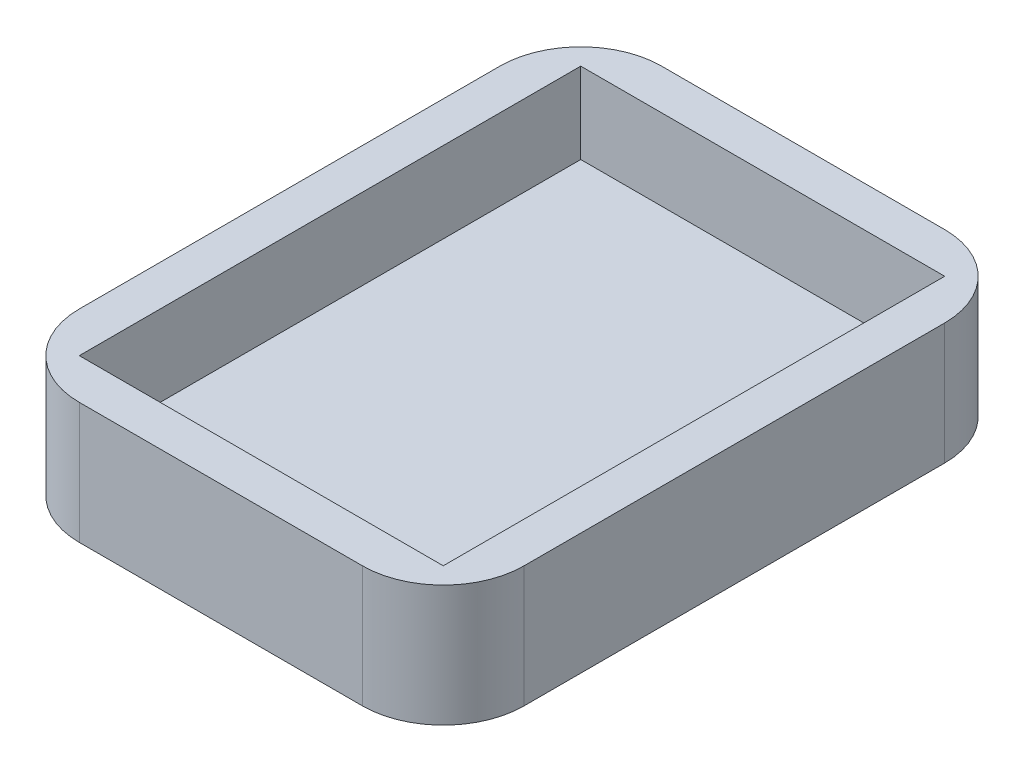
SolidWorks part; units mm, degrees
ref_plane "Front Plane" through (0, 0, 0) normal (0, 0, 1) x (1, 0, 0)
ref_plane "Top Plane" through (0, 0, 0) normal (0, 1, 0) x (1, 0, 0)
ref_plane "Right Plane" through (0, 0, 0) normal (1, 0, 0) x (0, 0, -1)
sketch "Sketch2" plane through (0, 0, 0) normal (0, 1, 0) x (1, 0, 0)
  line L1 (0, 0) -> (45, 0)
  line L2 (0, 0) -> (0, 62)
  line L3 (0, 62) -> (45, 62)
  line L4 (45, 0) -> (45, 62)
  dimension "D1" = 45
  dimension "D2" = 62
extrude "Boss-Extrude1" add sketch "Sketch2" along normal blind 5
sketch "Sketch3" plane through (0, 5, 0) normal (0, 1, 0) x (1, 0, 0)
  line L0 (50, -5) -> (50, 67)
  line L1 (50, 67) -> (-5, 67)
  line L2 (-5, 67) -> (-5, -5)
  line L3 (-5, -5) -> (50, -5)
  line L4 (0, 62) -> (0, 0)
  line L5 (0, 0) -> (45, 0)
  line L6 (45, 0) -> (45, 62)
  line L7 (45, 62) -> (0, 62)
  line L8 (0, 62) -> (0, 0)
  line L9 (0, 0) -> (45, 0)
  line L10 (45, 0) -> (45, 62)
  line L11 (45, 62) -> (0, 62)
  dimension "D1" = 0
  dimension "D2" = 5
extrude "Boss-Extrude2" add sketch "Sketch3" along normal blind 10 and the other way blind 5
fillet "Fillet1" radius 10 4 edges at (-5, 7.5, -67) (50, 7.5, 5) (50, 7.5, -67) (-5, 7.5, 5)
